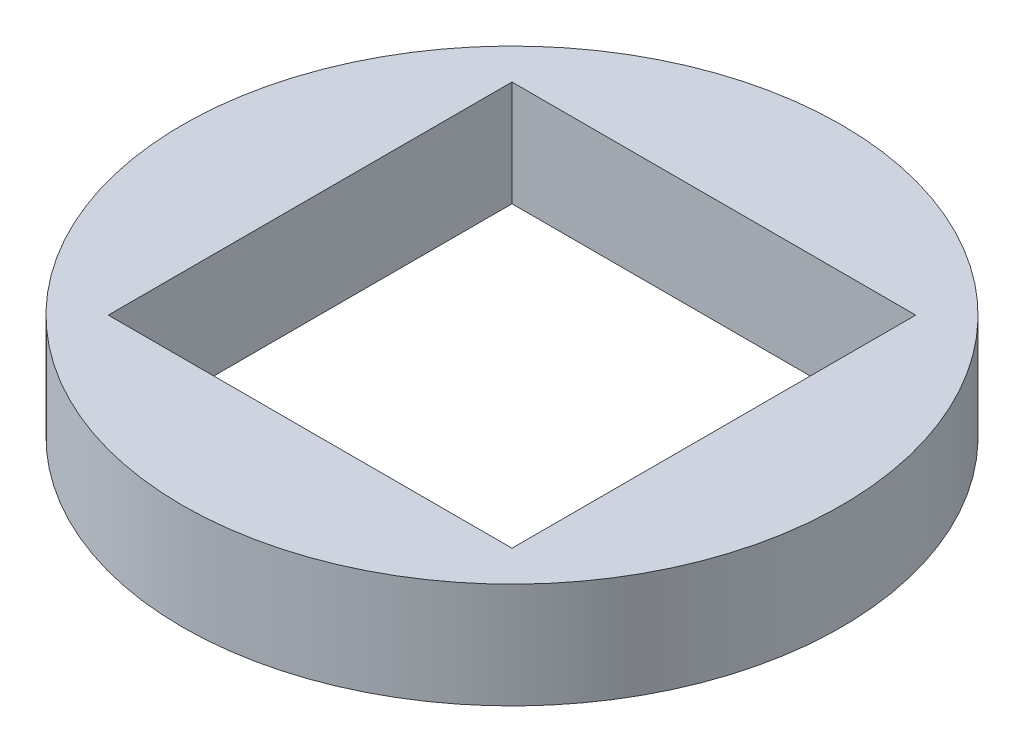
SolidWorks part; units mm, degrees
ref_plane "Front Plane" through (0, 0, 0) normal (0, 0, 1) x (1, 0, 0)
ref_plane "Top Plane" through (0, 0, 0) normal (0, 1, 0) x (1, 0, 0)
ref_plane "Right Plane" through (0, 0, 0) normal (1, 0, 0) x (0, 0, -1)
sketch "Sketch1" plane through (0, 0, 0) normal (0, 1, 0) x (1, 0, 0)
  line L1 (4.8617, -4.8617) -> (-4.8617, -4.8617)
  line L2 (4.8617, -4.8617) -> (4.8617, 4.8617)
  line L3 (4.8617, 4.8617) -> (-4.8617, 4.8617)
  line L4 (-4.8617, -4.8617) -> (-4.8617, 4.8617)
  line L5 (4.8617, -4.8617) -> (-4.8617, 4.8617) construction
  line L6 (4.8617, 4.8617) -> (-4.8617, -4.8617) construction
  circle A0 centre (0, 0) radius 7.9375
  dimension "D3" = 15.875
  dimension "D1" = 9.7234
  dimension "D2" = 9.7234
extrude "Boss-Extrude1" add sketch "Sketch1" along normal blind 2.54
